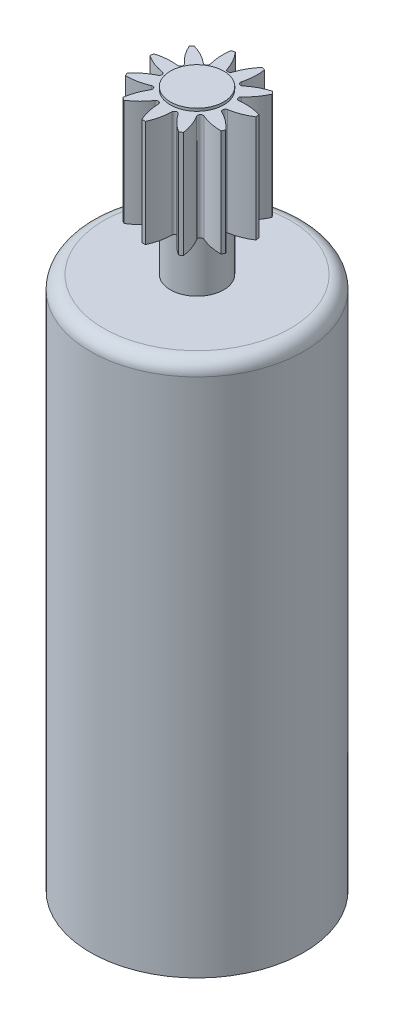
SolidWorks part; units mm, degrees
ref_plane "前视基准面" through (0, 0, 0) normal (0, 0, 1) x (1, 0, 0)
ref_plane "上视基准面" through (0, 0, 0) normal (0, 1, 0) x (1, 0, 0)
ref_plane "右视基准面" through (0, 0, 0) normal (1, 0, 0) x (0, 0, -1)
sketch "草图2" plane through (0, 0, 0) normal (0, 0, 1) x (1, 0, 0)
  line L0 (0, 0) -> (0, 26.1)
  line L1 (0, 26.1) -> (1, 26.1)
  line L2 (1, 26.1) -> (1, 26)
  line L3 (1, 26) -> (2, 26)
  line L4 (2, 26) -> (2, 22)
  line L5 (2, 22) -> (1, 22)
  line L6 (1, 22) -> (1, 20)
  line L7 (1, 20) -> (3.5, 20)
  line L8 (4, 19.5) -> (4, 0)
  line L9 (4, 0) -> (0, 0)
  arc A0 (3.5, 20) -> (4, 19.5) centre (3.5, 19.5) cw
  point P14 (4, 20)
  dimension "D9" = 0.5
  dimension "D1" = 26.1
  dimension "D2" = 1
  dimension "D3" = 0.1
  dimension "D4" = 4
  dimension "D5" = 1
  dimension "D6" = 3
  dimension "D7" = 4
  dimension "D8" = 2
revolve "旋转1" add sketch "草图2" angle 360 about L0
sketch "草图8" plane through (0, 26, 0) normal (0, 1, 0) x (1, 0, 0)
  line L0 (0, 0) -> (0, 3.0876) construction
  circle A0 centre (0, 0) radius 2 construction
  arc A1 (-0.5, 1.9365) -> (0.5, 1.9365) centre (0, 0) cw
  circle A2 centre (0, 0) radius 2 construction
  arc A3 (0.5, 1.9365) -> (0.0953, 1.2198) centre (2.002, 0.6158) ccw
  arc A4 (0.0953, 1.2198) -> (-0.0953, 1.2198) centre (0, 1.25) cw
  arc A5 (-0.5, 1.9365) -> (-0.0953, 1.2198) centre (-2.002, 0.6158) cw
  point P6 (0, 2)
  dimension "D2" = 2
  dimension "D3" = 0.1
  dimension "D1" = 1
  dimension "D4" = 0.75
extrude "切除-拉伸1" cut sketch "草图8" against normal blind 5
pattern_circular "阵列(圆周)1" count 11 over 360 about axis through (0, 0, 0) along (0, 1, 0) of "切除-拉伸1"
